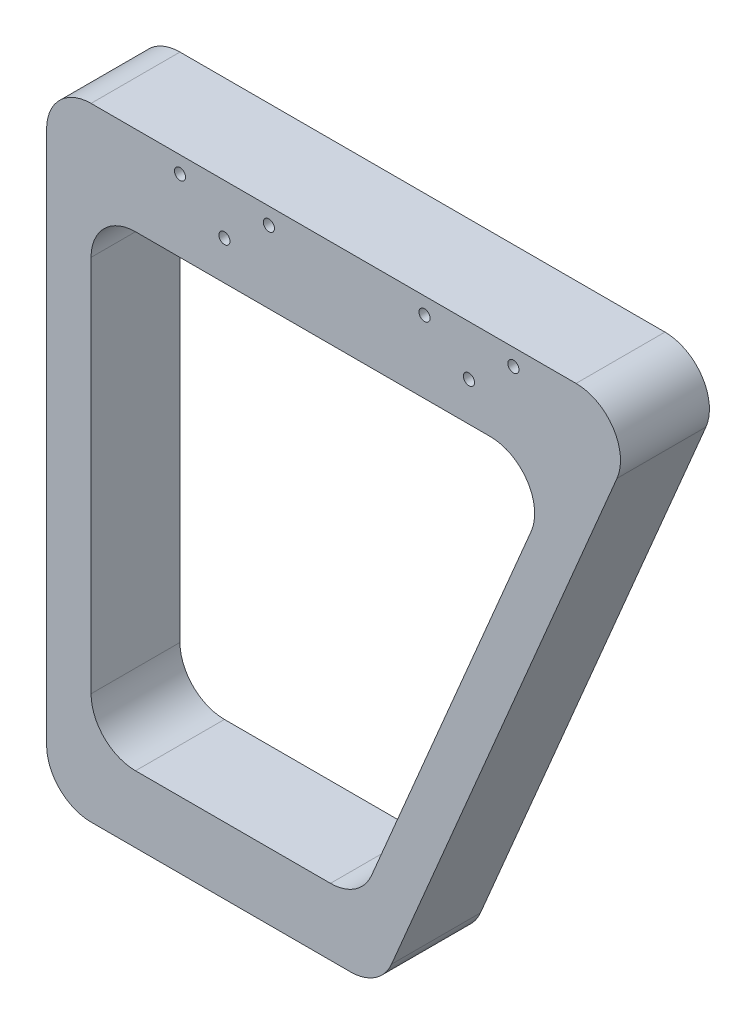
SolidWorks part; units mm, degrees
ref_plane "Front Plane" through (0, 0, 0) normal (0, 0, 1) x (1, 0, 0)
ref_plane "Top Plane" through (0, 0, 0) normal (0, 1, 0) x (1, 0, 0)
ref_plane "Right Plane" through (0, 0, 0) normal (1, 0, 0) x (0, 0, -1)
sketch "Sketch1" plane through (0, 0, 0) normal (0, 0, 1) x (1, 0, 0)
  line L0 (-160.6583, -135.3201) -> (-42.3163, 144.6799)
  line L13 (-310.6583, -135.3201) -> (289.3417, -135.3201)
  line L14 (-310.6583, -135.3201) -> (-310.6583, 144.6799)
  line L15 (-310.6583, 144.6799) -> (289.3417, 144.6799)
  line L16 (289.3417, -135.3201) -> (289.3417, 144.6799)
  line L17 (-80.9353, 104.6799) -> (-182.1122, -134.7071)
  line L19 (-290.6583, -105.3201) -> (-290.6583, 104.6799)
  line L20 (-290.6583, 104.6799) -> (-80.9353, 104.6799)
  line L21 (269.3417, -105.3201) -> (269.3417, 104.6799)
  line L22 (-37.5093, 104.6799) -> (269.3417, 104.6799)
  line L23 (-126.2658, -105.3201) -> (-37.5093, 104.6799)
  line L24 (269.3417, -105.3201) -> (-126.2658, -105.3201)
  line L25 (-169.6917, -105.3201) -> (-290.6583, -105.3201)
  point P0 (-124.0085, -88.9469)
  point P9 (-124.0085, -88.9469)
  dimension "D1" = 600
  dimension "D2" = 450
  dimension "D3" = 20
  dimension "D4" = 40
  dimension "D5" = 20
  dimension "D6" = 268.3419
  dimension "D7" = 20
  dimension "D8" = 20
  dimension "D9" = 280
  dimension "D10" = 30
extrude "Boss-Extrude2" add sketch "Sketch1" along normal blind 40
fillet "Fillet3" radius 20 8 edges at (-310.6583, 144.6799, 20) (-310.6583, -135.3201, 20) (-160.6583, -135.3201, 20) (-42.3163, 144.6799, 20) (-290.6583, 104.6799, 20) (-290.6583, -105.3201, 20) (-169.6917, -105.3201, 20) (-80.9353, 104.6799, 20)
sketch "Sketch2" plane through (0, 0, 40) normal (0, 0, 1) x (1, 0, 0)
  line L3 (-310.6583, -115.3201) -> (-310.6583, 124.6799) construction
  circle A0 centre (-250.6583, 137.1799) radius 2.5
  circle A1 centre (-210.6583, 137.1799) radius 2.5
  circle A2 centre (-230.6583, 122.1799) radius 2.5
  dimension "D2" = 5
  dimension "D3" = 5
  dimension "D4" = 40
  dimension "D6" = 5
  dimension "D7" = 20
  dimension "D1" = 80
extrude "Cut-Extrude1" cut sketch "Sketch2" against normal blind 10
ref_plane "Plane1" through (-175.6583, 0, 0) normal (-1, 0, 0) x (0, 0, 1)
mirror "Mirror1" about plane through (-175.6583, 0, 0) normal (-1, 0, 0) of "Cut-Extrude1"
